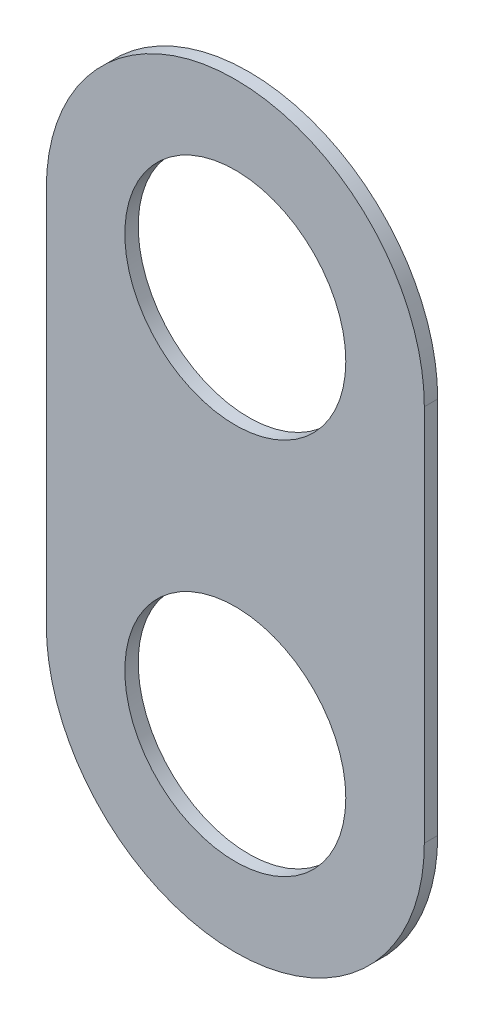
SolidWorks part; units mm, degrees
material "ASTM A36 Steel"
ref_plane "Front Plane" through (0, 0, 0) normal (0, 0, 1) x (1, 0, 0)
ref_plane "Top Plane" through (0, 0, 0) normal (0, 1, 0) x (1, 0, 0)
ref_plane "Right Plane" through (0, 0, 0) normal (1, 0, 0) x (0, 0, -1)
sketch "Sketch1" plane through (0, 0, 0) normal (0, 0, 1) x (1, 0, 0)
  line L0 (0, 24.7987) -> (0, -13.3013)
  line L1 (38.1, 24.7987) -> (38.1, -13.3013)
  arc A0 (38.1, 24.7987) -> (0, 24.7987) centre (19.05, 24.7987) ccw
  arc A1 (0, -13.3013) -> (38.1, -13.3013) centre (19.05, -13.3013) ccw
  circle A2 centre (19.05, 24.7987) radius 11.1354
  circle A3 centre (19.05, -13.3013) radius 11.1354
  point P11 (19.05, 22.3942)
  point P12 (19.05, 43.8487)
  point P13 (19.05, -32.3513)
  point P14 (19.05, 17.8282)
  point P15 (0, 0)
  point P16 (19.05, 17.7117)
  point P17 (19.7614, -32.8247)
  point P18 (0, 0)
  point P19 (0, 0)
  point P20 (19.05, 22.6512)
  point P21 (0, 0)
  dimension "D6" = 22.2707
  dimension "D7" = 22.2707
  dimension "D1" = 38.1
  dimension "D2" = 38.1
  dimension "D3" = 76.2
extrude "Boss-Extrude1" add sketch "Sketch1" along normal blind 1.3489
equation "\"P\"= 300'Transferred Tensile Load [lbf]"
equation "\"sigma_allow\"= 9064.86'Allowable Tensile Stress [psi] "
equation "\"E\"= 29007547.53'Elastic Modulus (ASTM A36 Steel) [psi] "
equation "\"delta_max\"= 0.005'Maximum Allowed Deflection Limit [in] "
equation "\"w_link\"= 1.50'Link Overall Width [in] "
equation "\"L_link\"= 3.0'Link Total Length [in] "
equation "\"d_hole\"= 0.8768'Pin Hole Diameter [in] "
equation "\"center_dist\"= 1.5'Hole Center-to-Center Distance [in]"
equation "\"A_net_req\"= \"P\" / \"sigma_allow\"'Required Minimum Net Cross-Sectional Area [in^2] "
equation "\"w_net\"= \"w_link\" - \"d_hole\"'Net Width Across Hole Section [in] "
equation "\"t_stress\"= \"A_net_req\" / \"w_net\"'Calculated Minimum Stress Thickness [in] "
equation "\"t_nominal\"= 0.250'Selected Nominal Plate Thickness [in] "
equation "\"A_net_act\"= ( \"w_link\" - \"d_hole\" ) * \"t_stress\"'Actual Net Cross-Sectional Area [in^2] "
equation "\"delta_act\"= ( \"P\" * \"L_link\" ) / ( \"A_net_act\" * \"E\" )'Actual Axial Extension Deflection [in] (Passes ≤0.005\" in\" ) "
equation "\"D1@Sketch1\"=\"w_link\""
equation "\"D2@Sketch1\"=\"center_dist\""
equation "\"D3@Sketch1\"=\"L_link\""
equation "\"D6@Sketch1\"=\"d_hole\""
equation "\"D7@Sketch1\"=\"d_hole\""
equation "\"D1@Boss-Extrude1\"=\"t_stress\""
